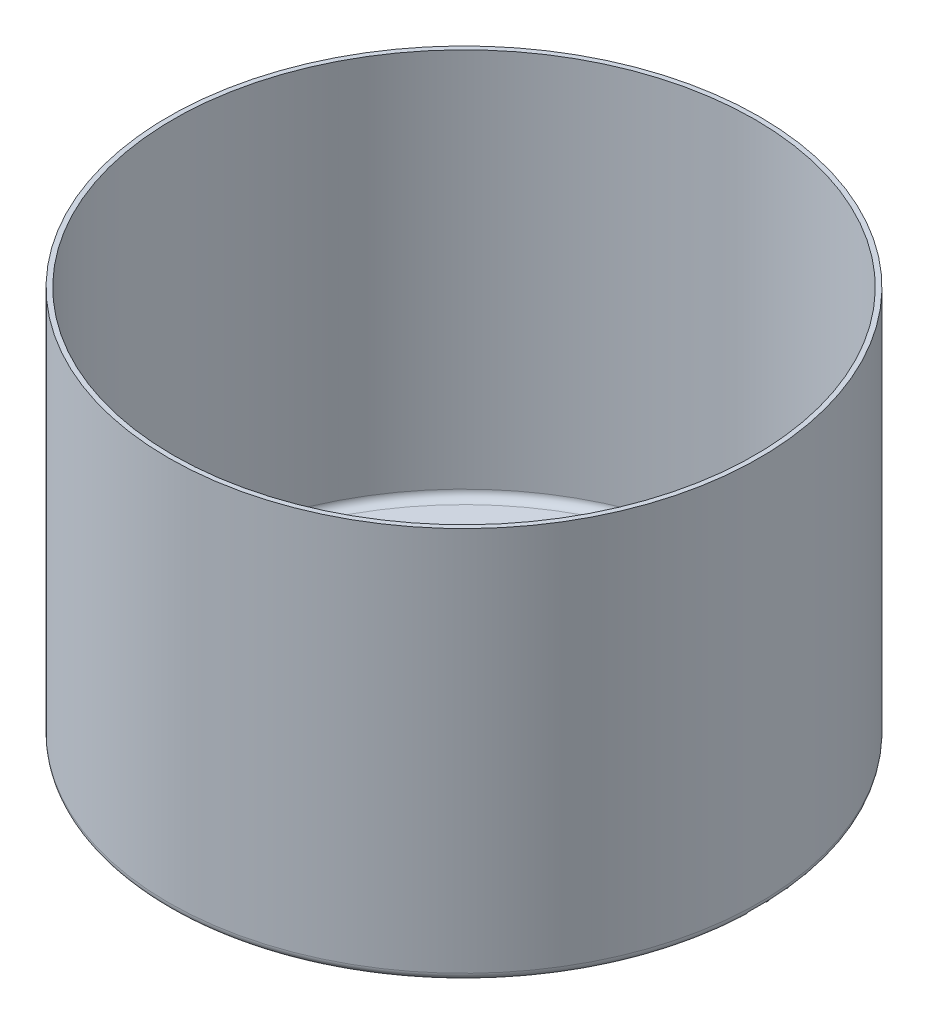
SolidWorks part; units mm, degrees
ref_plane "Front Plane" through (0, 0, 0) normal (0, 0, 1) x (1, 0, 0)
ref_plane "Top Plane" through (0, 0, 0) normal (0, 1, 0) x (1, 0, 0)
ref_plane "Right Plane" through (0, 0, 0) normal (1, 0, 0) x (0, 0, -1)
sketch "Compartment" plane through (0, 0, 0) normal (0, 0, 1) x (1, 0, 0)
  line L3 (95.504, -80) -> (0, -80)
  line L6 (93.98, 47) -> (95.504, 47)
  line L9 (93.98, 47) -> (93.98, -78.476)
  line L10 (93.98, -78.476) -> (0, -78.476)
  line L11 (0, -78.476) -> (0, -80)
  line L14 (95.504, 47) -> (95.504, -80)
  dimension "D1" = 125.476
  dimension "D2" = 1.524
  dimension "D5" = 93.98
  dimension "D6" = 1.524
  dimension "D9" = 80
ref_axis "Axis1" through (0, 0, 0) along (0, 1, 0)
revolve "Revolve1" add sketch "Compartment" angle 360 about axis through (0, 0, 0) along (0, 1, 0)
sketch "Motor Hole" plane through (0, -80, 0) normal (0, -1, 0) x (1, 0, 0)
  circle A0 centre (0, 0) radius 18.415
  circle A1 centre (0, 63.5) radius 3.25
  circle A2 centre (63.5, 0) radius 3.25
  circle A3 centre (0, -63.5) radius 3.25
  circle A4 centre (-63.5, 0) radius 3.25
  dimension "D1" = 36.83
  dimension "D2" = 6.5
  dimension "D3" = 63.5
  dimension "D4" = 63.5
  dimension "D5" = 63.5
  dimension "D6" = 63.5
extrude "Cut-Extrude2" cut sketch "Motor Hole" against normal up to next
fillet "Fillet1" radius 2.54 2 edges at (0, -78.476, -93.98) (0, -80, -95.504)
